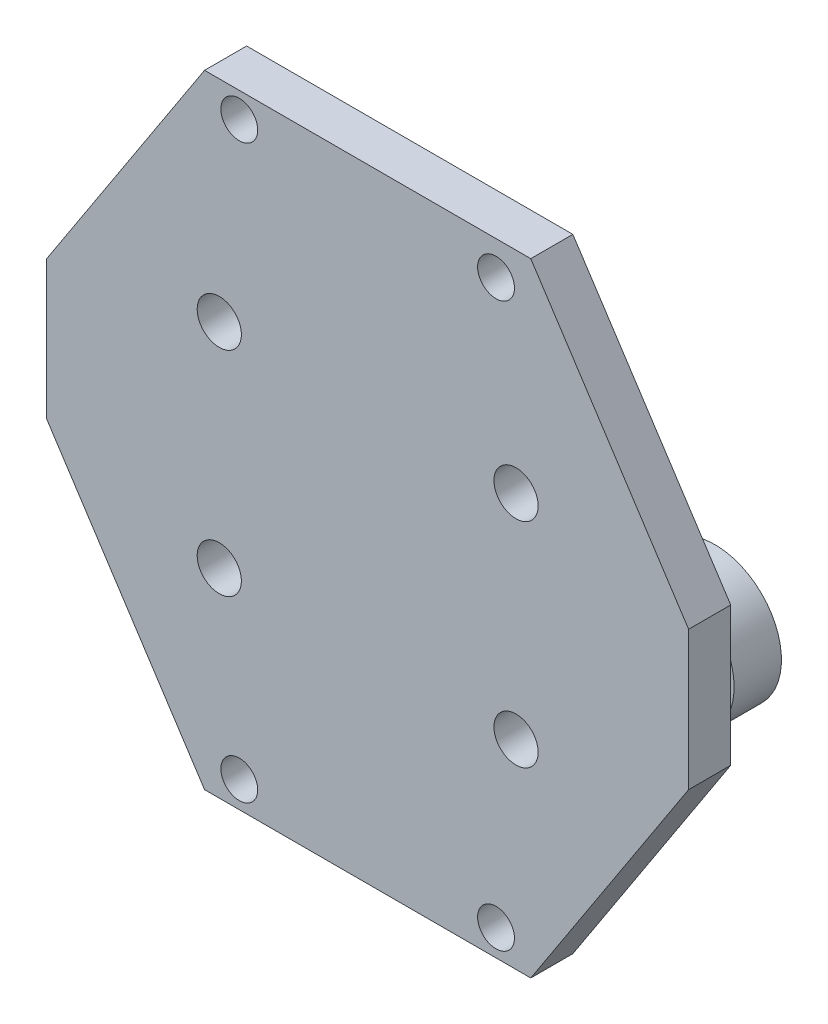
SolidWorks part; units mm, degrees
ref_plane "Alzado" through (0, 0, 0) normal (0, 0, 1) x (1, 0, 0)
ref_plane "Planta" through (0, 0, 0) normal (0, 1, 0) x (1, 0, 0)
ref_plane "Vista lateral" through (0, 0, 0) normal (1, 0, 0) x (0, 0, -1)
sketch "Croquis1" plane through (0, 0, 0) normal (0, 0, 1) x (1, 0, 0)
  line L1 (0, 0) -> (22, 0)
  line L2 (0, 0) -> (0, 55.2)
  line L3 (0, 55.2) -> (22, 55.2)
  line L4 (22, 0) -> (22, 55.2)
  dimension "D1" = 55.2
  dimension "D2" = 22
extrude "Saliente-Extruir1" add sketch "Croquis1" along normal blind 4
sketch "Croquis2" plane through (0, 55.2, 0) normal (0, 1, 0) x (1, 0, 0)
  line L0 (22, 0) -> (0, 0) construction
  line L1 (4.95, 0) -> (17.05, 0)
  line L2 (4.95, 0) -> (4.95, -4)
  line L3 (4.95, -4) -> (17.05, -4)
  line L4 (17.05, 0) -> (17.05, -4)
  line L5 (22, -4) -> (0, -4) construction
  line L6 (0, -4) -> (0, 0) construction
  dimension "D1" = 12.1
  dimension "D2" = 4.95
extrude "Cortar-Extruir1" cut sketch "Croquis2" against normal blind 9.6
sketch "Croquis3" plane through (0, 0, 0) normal (0, -1, 0) x (1, 0, 0)
  line L0 (0, 4) -> (22, 4) construction
  line L1 (4.95, 4) -> (17.05, 4)
  line L2 (4.95, 4) -> (4.95, 0)
  line L3 (4.95, 0) -> (17.05, 0)
  line L4 (17.05, 4) -> (17.05, 0)
  line L5 (0, 0) -> (22, 0) construction
  line L6 (0, 4) -> (0, 0) construction
  line L7 (22, 4) -> (22, 0) construction
  dimension "D1" = 4.95
  dimension "D2" = 4.95
extrude "Cortar-Extruir2" cut sketch "Croquis3" against normal blind 9.6
sketch "Croquis5" plane through (0, 9.6, 0) normal (0, -1, 0) x (1, 0, 0)
  line L0 (7.4, 4) -> (14.6, 4)
  line L1 (17.05, 4) -> (4.95, 4) construction
  line L2 (4.95, -1.5) -> (17.05, -1.5)
  arc A2 (7.4, 4) -> (4.95, -1.5) centre (12.4499, -1.5452) ccw
  arc A3 (17.05, -1.5) -> (14.6, 4) centre (9.5501, -1.5452) ccw
  dimension "D1" = 7.2
  dimension "D2" = 2.45
extrude "Cortar-Extruir3" cut sketch "Croquis5" against normal blind 16
sketch "Croquis7" plane through (0, 45.6, 0) normal (0, 1, 0) x (1, 0, 0)
  line L5 (4.95, -4) -> (17.05, -4) construction
  line L11 (4.95, 1.5) -> (17.05, 1.5)
  line L12 (7.4, -4) -> (14.6, -4)
  arc A3 (4.95, 1.5) -> (7.4, -4) centre (12.4499, 1.5452) ccw
  arc A4 (14.6, -4) -> (17.05, 1.5) centre (9.5501, 1.5452) ccw
extrude "Cortar-Extruir4" cut sketch "Croquis7" against normal blind 16
sketch "Croquis9" plane through (0, 0, 0) normal (0, 0, -1) x (-1, 0, 0)
  line L1 (-16.8892, 29.6) -> (-5.1108, 29.6)
  line L2 (-16.8892, 29.6) -> (-16.8892, 25.6)
  line L3 (-16.8892, 25.6) -> (-5.1108, 25.6)
  line L4 (-5.1108, 29.6) -> (-5.1108, 25.6)
extrude "Cortar-Extruir5" cut sketch "Croquis9" against normal blind 2
sketch "Croquis11" plane through (0, 55.2, 0) normal (0, 1, 0) x (1, 0, 0)
  line L0 (0, -4) -> (4.95, -4) construction
  line L1 (4.95, -4) -> (4.95, 0) construction
  line L2 (4.95, 0) -> (0, 0) construction
  line L3 (0, 0) -> (0, -4) construction
  line L4 (22, 0) -> (17.05, 0) construction
  line L5 (17.05, 0) -> (17.05, -4) construction
  line L6 (17.05, -4) -> (22, -4) construction
  line L7 (22, -4) -> (22, 0) construction
  line L8 (0, -4) -> (4.95, -4)
  line L9 (4.95, -4) -> (4.95, 0)
  line L10 (4.95, 0) -> (0, 0)
  line L11 (0, 0) -> (0, -4)
  line L12 (22, 0) -> (17.05, 0)
  line L13 (17.05, 0) -> (17.05, -4)
  line L14 (17.05, -4) -> (22, -4)
  line L15 (22, -4) -> (22, 0)
extrude "Saliente-Extruir3" add sketch "Croquis11" along normal blind 2
sketch "Croquis12" plane through (4.95, 0, 0) normal (1, 0, 0) x (0, 0, -1)
  line L0 (-4, 57.2) -> (0, 57.2)
  line L1 (0, 57.2) -> (0, 55.4)
  line L2 (0, 45.6) -> (0, 57.2) construction
  line L3 (0, 55.4) -> (-4, 55.4)
  line L4 (-4, 45.6) -> (-4, 57.2) construction
  line L5 (-4, 55.4) -> (-4, 57.2)
extrude "Saliente-Extruir4" add sketch "Croquis12" along normal blind 12.1
sketch "Croquis13" plane through (0, 0, 0) normal (0, -1, 0) x (1, 0, 0)
  line L0 (22, 4) -> (17.05, 4) construction
  line L1 (17.05, 4) -> (17.05, 0) construction
  line L2 (17.05, 0) -> (22, 0) construction
  line L3 (22, 0) -> (22, 4) construction
  line L4 (0, 0) -> (4.95, 0) construction
  line L5 (4.95, 0) -> (4.95, 4) construction
  line L6 (4.95, 4) -> (0, 4) construction
  line L7 (0, 4) -> (0, 0) construction
  line L8 (22, 4) -> (17.05, 4)
  line L9 (17.05, 4) -> (17.05, 0)
  line L10 (17.05, 0) -> (22, 0)
  line L11 (22, 0) -> (22, 4)
  line L12 (0, 0) -> (4.95, 0)
  line L13 (4.95, 0) -> (4.95, 4)
  line L14 (4.95, 4) -> (0, 4)
  line L15 (0, 4) -> (0, 0)
extrude "Saliente-Extruir5" add sketch "Croquis13" along normal blind 2
sketch "Croquis14" plane through (4.95, 0, 0) normal (1, 0, 0) x (0, 0, -1)
  line L0 (-4, 9.6) -> (-4, -2) construction
  line L1 (0, -2) -> (-4, -2)
  line L2 (0, -2) -> (0, -0.2)
  line L3 (0, -0.2) -> (-4, -0.2)
  line L4 (-4, -2) -> (-4, -0.2)
extrude "Saliente-Extruir6" add sketch "Croquis14" along normal blind 12.1
sketch "Croquis17" plane through (0, 0, 0) normal (-1, 0, 0) x (0, 0, 1)
  line L4 (0, 57.2) -> (0, -2)
  line L5 (0, -2) -> (4, -2)
  line L6 (4, -2) -> (4, 57.2)
  line L7 (4, 57.2) -> (0, 57.2)
  line L8 (0, 57.2) -> (0, -2)
  line L10 (4, -2) -> (4, 57.2)
  line L13 (4, 57.2) -> (0, 57.2)
  line L15 (0, -2) -> (4, -2)
  dimension "D1" = 0
extrude "Saliente-Extruir8" add sketch "Croquis17" along normal blind 11.5 contours L8 L15 L10 L13
sketch "Croquis18" plane through (22, 0, 0) normal (1, 0, 0) x (0, 0, -1)
  line L4 (0, -2) -> (0, 57.2)
  line L5 (0, 57.2) -> (-4, 57.2)
  line L6 (-4, 57.2) -> (-4, -2)
  line L7 (-4, -2) -> (0, -2)
  line L8 (0, -2) -> (0, 57.2)
  line L10 (-4, 57.2) -> (-4, -2)
  line L11 (-4, -2) -> (0, -2)
  line L13 (0, 57.2) -> (-4, 57.2)
  dimension "D1" = 0
extrude "Saliente-Extruir9" add sketch "Croquis18" along normal blind 11.5
sketch "Croquis19" plane through (0, 0, 0) normal (0, 0, -1) x (-1, 0, 0)
  line L0 (11.5, -2) -> (-33.5, -2) construction
  line L3 (11.5, 57.2) -> (11.5, -2) construction
  circle A0 centre (-23.2, 54) radius 1.75
  circle A1 centre (1.2, 54.8) radius 1.75
  circle A2 centre (1.2, 0.5) radius 1.75
  circle A3 centre (-23.2, 0.5) radius 1.75
  dimension "D1" = 3.5
  dimension "D2" = 3.5
  dimension "D3" = 3.5
  dimension "D4" = 3.5
  dimension "D5" = 2.5
  dimension "D6" = 2.5
  dimension "D7" = 53.5
  dimension "D8" = 54.3
  dimension "D9" = 10.3
  dimension "D10" = 24.4
  dimension "D11" = 24.4
  dimension "D12" = 10.3
extrude "Cortar-Extruir6" cut sketch "Croquis19" against normal blind 11.5
ref_plane "Plano2" through (0, 0, -7.5) normal (0, 0, -1) x (-1, 0, 0)
sketch "Croquis27" plane through (0, 0, 0) normal (0, 0, -1) x (-1, 0, 0)
  line L1 (-17.05, 55.4) -> (-4.95, 55.4)
  line L2 (-17.05, 55.4) -> (-17.05, -0.2)
  line L3 (-17.05, -0.2) -> (-4.95, -0.2)
  line L4 (-4.95, 55.4) -> (-4.95, -0.2)
extrude "Cortar-Extruir8" cut sketch "Croquis27" against normal blind 10
sketch "Croquis28" plane through (0, 55.4, 0) normal (0, -1, 0) x (1, 0, 0)
  line L4 (4.95, 4) -> (4.95, 0)
  line L5 (4.95, 0) -> (17.05, 0)
  line L6 (17.05, 0) -> (17.05, 4)
  line L7 (17.05, 4) -> (4.95, 4)
  line L8 (4.95, 4) -> (4.95, 0)
  line L9 (4.95, 0) -> (17.05, 0)
  line L10 (17.05, 0) -> (17.05, 4)
  line L11 (17.05, 4) -> (4.95, 4)
  dimension "D1" = 0
extrude "Saliente-Extruir10" add sketch "Croquis28" along normal blind 55.6
sketch "Croquis33" plane through (-11.5, 0, 0) normal (-1, 0, 0) x (0, 0, 1)
  line L6 (4, 57.2) -> (0, 57.2)
  line L7 (0, 57.2) -> (0, -2)
  line L10 (0, -2) -> (4, -2)
  line L11 (4, -2) -> (4, 57.2)
  line L12 (4, 57.2) -> (0, 57.2)
  line L13 (0, 57.2) -> (0, -2)
  line L16 (0, -2) -> (4, -2)
  line L17 (4, -2) -> (4, 57.2)
  dimension "D1" = 0
extrude "Saliente-Extruir13" add sketch "Croquis33" along normal blind 8
sketch "Croquis30" plane through (0, 0, 0) normal (0, 0, -1) x (-1, 0, 0)
  circle A0 centre (-25.1, 37.1948) radius 2.1
  circle A1 centre (-25.1, 16.9253) radius 2.1
  circle A2 centre (3.1, 37.1948) radius 2.1
  circle A3 centre (3.1, 16.9253) radius 2.1
extrude "Cortar-Extruir9" cut sketch "Croquis30" against normal blind 10
sketch "Croquis32" plane through (33.5, 0, 0) normal (1, 0, 0) x (0, 0, -1)
  line L4 (-4, -2) -> (0, -2)
  line L5 (0, -2) -> (0, 57.2)
  line L6 (0, 57.2) -> (-4, 57.2)
  line L7 (-4, 57.2) -> (-4, -2)
  line L8 (-4, -2) -> (0, -2)
  line L9 (0, -2) -> (0, 57.2)
  line L10 (0, 57.2) -> (-4, 57.2)
  line L11 (-4, 57.2) -> (-4, -2)
  dimension "D1" = 0
extrude "Saliente-Extruir12" add sketch "Croquis32" along normal blind 8
sketch "Croquis29" plane through (0, 0, 0) normal (0, 0, -1) x (-1, 0, 0)
  line L0 (-32.0999, 32.2019) -> (-32.0999, 22.9981)
  line L2 (8.8371, 23.3279) -> (8.8371, 31.8721)
  line L3 (-11, 57.2) -> (-11, 11.5937) construction
  line L4 (-41.5, 57.2) -> (19.5, 57.2) construction
  line L5 (19.5, 57.2) -> (19.5, -2) construction
  line L6 (-41.5, -2) -> (-41.5, 57.2) construction
  line L7 (19.5, 27.6) -> (-11, 27.6) construction
  line L8 (-32.0999, 32.2019) -> (-32.0999, 32.9274)
  line L9 (-32.0999, 22.9981) -> (-32.0999, 22.2726)
  arc A1 (8.8371, 23.3279) -> (8.8371, 31.8721) centre (13.5, 27.6) ccw
  arc A2 (-32.0999, 32.9274) -> (-32.0999, 22.2726) centre (-35.5, 27.6) ccw
  dimension "D1" = 6
  dimension "D2" = 6
  dimension "D3" = 0
  dimension "D4" = 0
extrude "Saliente-Extruir11" add sketch "Croquis29" along normal blind 4.5
sketch "Croquis35" plane through (0, 0, -7.5) normal (0, 0, -1) x (-1, 0, 0)
  line L0 (-11, 57.2) -> (-11, -5.7151) construction
  line L1 (-35.5, 32.6) -> (-35.5, 22.6)
  line L2 (-41.5, 57.2) -> (19.5, 57.2) construction
  arc A2 (-35.5, 32.6) -> (-35.5, 22.6) centre (-35.5, 27.6) ccw
revolve "Cortar-Revolución1" cut sketch "Croquis35" angle 360 about L1
sketch "Croquis36" plane through (0, 0, -7.5) normal (0, 0, -1) x (-1, 0, 0)
  line L0 (13.5, 32.6) -> (13.5, 22.6)
  arc A0 (13.5, 22.6) -> (13.5, 32.6) centre (13.5, 27.6) ccw
revolve "Cortar-Revolución2" cut sketch "Croquis36" angle 360 about L0
sketch "Croquis37" plane through (0, 0, 4) normal (0, 0, 1) x (1, 0, 0)
  line L0 (-19.5, 57.2) -> (-19.5, 34.2)
  line L1 (-19.5, -2) -> (-19.5, 57.2) construction
  line L2 (-19.5, 57.2) -> (-4.5, 57.2)
  line L3 (-19.5, 57.2) -> (41.5, 57.2) construction
  line L4 (41.5, 57.2) -> (26.5, 57.2)
  line L5 (41.5, 57.2) -> (41.5, 34.2)
  line L6 (41.5, 57.2) -> (41.5, -2) construction
  line L7 (-19.5, -2) -> (-19.5, 21)
  line L8 (-19.5, -2) -> (-4.5, -2)
  line L9 (41.5, -2) -> (-19.5, -2) construction
  line L10 (41.5, -2) -> (41.5, 21)
  line L11 (41.5, -2) -> (26.5, -2)
  line L12 (26.5, -2) -> (41.5, 21)
  line L13 (-4.5, 57.2) -> (-19.5, 34.2)
  line L14 (-19.5, 21) -> (-4.5, -2)
  line L15 (41.5, 34.2) -> (26.5, 57.2)
extrude "Cortar-Extruir10" cut sketch "Croquis37" against normal blind 8
